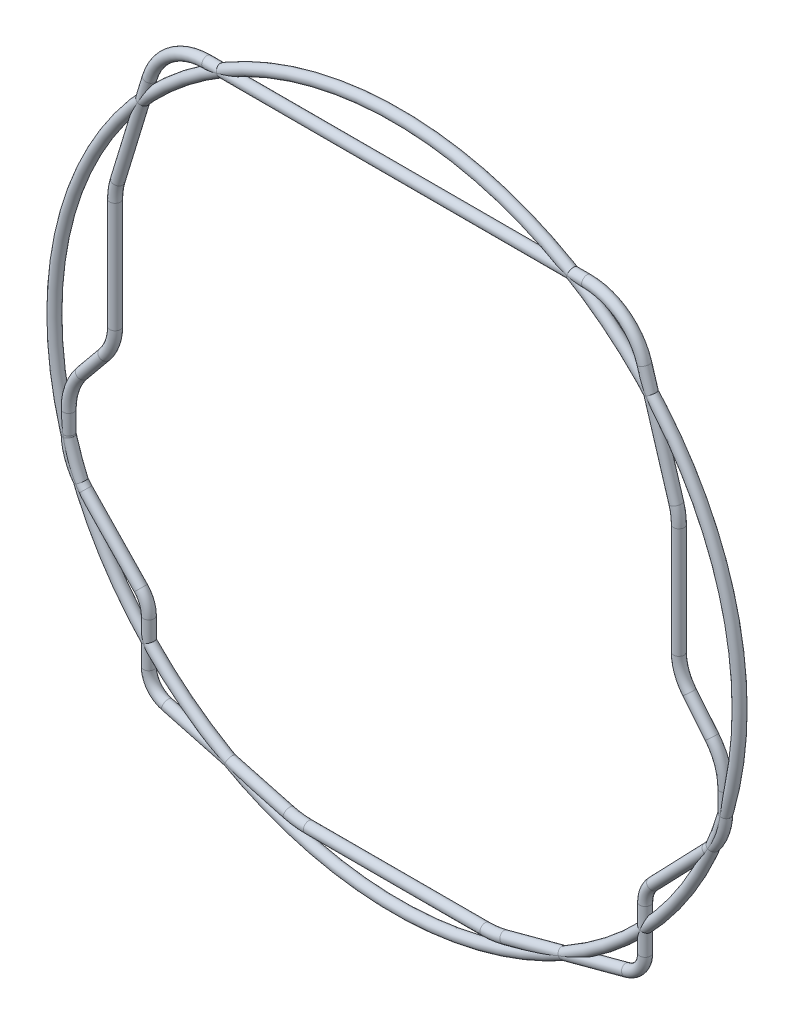
SolidWorks part; units mm, degrees
ref_plane "Front Plane" through (0, 0, 0) normal (0, 0, 1) x (1, 0, 0)
ref_plane "Top Plane" through (0, 0, 0) normal (0, 1, 0) x (1, 0, 0)
ref_plane "Right Plane" through (0, 0, 0) normal (1, 0, 0) x (0, 0, -1)
sketch "Sketch1" plane through (0, 0, 0) normal (0, 0, 1) x (1, 0, 0)
  line L0 (0, 0) -> (126.8104, 0) construction
  line L1 (-24.867, -87.5) -> (0, -87.5) construction
  line L2 (-53.5, 81) -> (53.5, 81) construction
  line L3 (67.8489, 70.3715) -> (76.8489, 40.8305) construction
  line L4 (77.5, 36.459) -> (77.5, 5.3573) construction
  line L5 (80.8939, -4.1452) -> (87.2061, -11.8548) construction
  line L6 (90.6, -21.3573) -> (90.6, -26.8454) construction
  line L7 (70.7917, -53.4876) -> (86.4125, -37.242) construction
  line L8 (68, -60.4187) -> (68, -72.8114) construction
  line L9 (64.2941, -77.6411) -> (30.0433, -86.8185) construction
  line L10 (24.867, -87.5) -> (0, -87.5) construction
  line L11 (-53.5, 82.9) -> (53.5, 82.9)
  line L12 (-64.2941, -77.6411) -> (-30.0433, -86.8185) construction
  line L13 (-68, -60.4187) -> (-68, -72.8114) construction
  line L14 (-70.7917, -53.4876) -> (-86.4125, -37.242) construction
  line L15 (-90.6, -21.3573) -> (-90.6, -26.8454) construction
  line L16 (-80.8939, -4.1452) -> (-87.2061, -11.8548) construction
  line L17 (-77.5, 36.459) -> (-77.5, 5.3573) construction
  line L18 (-67.8489, 70.3715) -> (-76.8489, 40.8305) construction
  line L19 (69.6664, 70.9253) -> (78.6664, 41.3842)
  line L20 (79.4, 36.459) -> (79.4, 5.3573)
  line L21 (82.364, -2.9415) -> (88.6762, -10.6512)
  line L22 (92.5, -21.3573) -> (92.5, -26.8454)
  line L23 (72.1613, -54.8045) -> (87.7821, -38.5589)
  line L24 (69.9, -60.4187) -> (69.9, -72.8114)
  line L25 (64.7859, -79.4763) -> (30.5351, -88.6538)
  line L26 (24.867, -89.4) -> (0, -89.4)
  line L27 (-24.867, -89.4) -> (0, -89.4)
  line L28 (-64.7859, -79.4763) -> (-30.5351, -88.6538)
  line L29 (-69.9, -60.4187) -> (-69.9, -72.8114)
  line L30 (-72.1613, -54.8045) -> (-87.7821, -38.5589)
  line L31 (-92.5, -21.3573) -> (-92.5, -26.8454)
  line L32 (-82.364, -2.9415) -> (-88.6762, -10.6512)
  line L33 (-79.4, 36.459) -> (-79.4, 5.3573)
  line L34 (-69.6664, 70.9253) -> (-78.6664, 41.3842)
  line L36 (0, 0) -> (0, 106.8179) construction
  arc A0 (53.5, 82.9) -> (69.6664, 70.9253) centre (53.5, 66) cw
  arc A1 (77.5, 5.3573) -> (80.8939, -4.1452) centre (92.5, 5.3573) ccw construction
  arc A2 (87.2061, -11.8548) -> (90.6, -21.3573) centre (75.6, -21.3573) cw construction
  arc A3 (90.6, -26.8454) -> (86.4125, -37.242) centre (75.6, -26.8454) cw construction
  arc A4 (76.8489, 40.8305) -> (77.5, 36.459) centre (62.5, 36.459) cw construction
  arc A5 (53.5, 81) -> (67.8489, 70.3715) centre (53.5, 66) cw construction
  arc A6 (70.7917, -53.4876) -> (68, -60.4187) centre (78, -60.4187) ccw construction
  arc A7 (68, -72.8114) -> (64.2941, -77.6411) centre (63, -72.8114) cw construction
  arc A8 (30.0433, -86.8185) -> (24.867, -87.5) centre (24.867, -67.5) cw construction
  arc A9 (-30.0433, -86.8185) -> (-24.867, -87.5) centre (-24.867, -67.5) ccw construction
  arc A10 (-68, -72.8114) -> (-64.2941, -77.6411) centre (-63, -72.8114) ccw construction
  arc A11 (-70.7917, -53.4876) -> (-68, -60.4187) centre (-78, -60.4187) cw construction
  arc A12 (-53.5, 81) -> (-67.8489, 70.3715) centre (-53.5, 66) ccw construction
  arc A13 (-76.8489, 40.8305) -> (-77.5, 36.459) centre (-62.5, 36.459) ccw construction
  arc A14 (-90.6, -26.8454) -> (-86.4125, -37.242) centre (-75.6, -26.8454) ccw construction
  arc A15 (-87.2061, -11.8548) -> (-90.6, -21.3573) centre (-75.6, -21.3573) ccw construction
  arc A16 (-77.5, 5.3573) -> (-80.8939, -4.1452) centre (-92.5, 5.3573) cw construction
  arc A17 (78.6664, 41.3842) -> (79.4, 36.459) centre (62.5, 36.459) cw
  arc A18 (79.4, 5.3573) -> (82.364, -2.9415) centre (92.5, 5.3573) ccw
  arc A19 (88.6762, -10.6512) -> (92.5, -21.3573) centre (75.6, -21.3573) cw
  arc A20 (92.5, -26.8454) -> (87.7821, -38.5589) centre (75.6, -26.8454) cw
  arc A21 (72.1613, -54.8045) -> (69.9, -60.4187) centre (78, -60.4187) ccw
  arc A22 (69.9, -72.8114) -> (64.7859, -79.4763) centre (63, -72.8114) cw
  arc A23 (30.5351, -88.6538) -> (24.867, -89.4) centre (24.867, -67.5) cw
  arc A24 (-30.5351, -88.6538) -> (-24.867, -89.4) centre (-24.867, -67.5) ccw
  arc A25 (-69.9, -72.8114) -> (-64.7859, -79.4763) centre (-63, -72.8114) ccw
  arc A26 (-72.1613, -54.8045) -> (-69.9, -60.4187) centre (-78, -60.4187) cw
  arc A27 (-92.5, -26.8454) -> (-87.7821, -38.5589) centre (-75.6, -26.8454) ccw
  arc A28 (-88.6762, -10.6512) -> (-92.5, -21.3573) centre (-75.6, -21.3573) ccw
  arc A29 (-79.4, 5.3573) -> (-82.364, -2.9415) centre (-92.5, 5.3573) cw
  arc A30 (-78.6664, 41.3842) -> (-79.4, 36.459) centre (-62.5, 36.459) ccw
  arc A31 (-53.5, 82.9) -> (-69.6664, 70.9253) centre (-53.5, 66) ccw
  point P57 (0, 81)
  point P102 (70.1123, -64.4364)
  point P103 (68, -64.4364)
  point P104 (71.611, -59.4574)
  point P106 (0, 0)
  point P107 (71.611, -59.4574)
  point P108 (68, -63.607)
  point P109 (70.2285, -63.607)
  point P110 (0, 0)
  point P111 (-68, -60.4187)
  dimension "D5" = 10
  dimension "D12" = 87.5
  dimension "D13" = 36.459
  dimension "D14" = 21.3573
  dimension "D15" = 78.618
  dimension "D16" = 49.7339
  dimension "D3" = 15
  dimension "D4" = 15
  dimension "D6" = 5
  dimension "D7" = 20
  dimension "D8" = 107
  dimension "D17" = 60.4187
  dimension "D18" = 87.754
  dimension "D19" = 26.8454
  dimension "D1" = 168.5
  dimension "D2" = 15
  dimension "D9" = 155
  dimension "D10" = 181.2
  dimension "D11" = 136
  dimension "D21" = 1.9
sketch "Sketch2" plane through (0, 0, 0) normal (1, 0, 0) x (0, 0, -1)
  line L0 (0, -88.6538) -> (0, -89.4) construction
  circle A0 centre (0, -89.4) radius 1.5
  dimension "D1" = 3
sweep "Sweep1" add profiles "Sketch2" path "Sketch1"
sketch "Sketch3" plane through (0, 0, 0) normal (1, 0, 0) x (0, 0, -1)
  line L0 (0, 0) -> (63.4243, 0) construction
  circle A0 centre (0, 96.5) radius 1.5
  dimension "D1" = 3
  dimension "D2" = 190
revolve "Revolve1" add sketch "Sketch3" angle 360 about L0
sketch "Sketch4" [suppressed] plane through (0, 0, 0) normal (0, 0, 1) x (1, 0, 0)
  line L0 (0, 0) -> (113.8842, 0) construction
  line L1 (0, 0) -> (0, 100.6817) construction
  line L2 (-83.1, 65.075) -> (-83.1, -45.129) construction
  line L3 (83.1, 65.075) -> (83.1, -45.129) construction
  line L4 (-68.1, 80.075) -> (68.1, 80.075) construction
  line L5 (-48.154, -80.075) -> (48.154, -80.075) construction
  line L6 (-78.7066, -55.7356) -> (-58.7606, -75.6816) construction
  line L7 (78.7066, -55.7356) -> (58.7606, -75.6816) construction
  line L14 (-48.154, -82.075) -> (48.154, -82.075)
  line L15 (80.1208, -57.1498) -> (60.1748, -77.0958)
  line L16 (85.1, 65.075) -> (85.1, -45.129)
  line L17 (-68.1, 82.075) -> (68.1, 82.075)
  line L18 (-85.1, 65.075) -> (-85.1, -45.129)
  line L19 (-80.1208, -57.1498) -> (-60.1748, -77.0958)
  arc A0 (83.1, 65.075) -> (68.1, 80.075) centre (68.1, 65.075) ccw construction
  arc A1 (-68.1, 80.075) -> (-83.1, 65.075) centre (-68.1, 65.075) ccw construction
  arc A2 (78.7066, -55.7356) -> (83.1, -45.129) centre (68.1, -45.129) ccw construction
  arc A3 (58.7606, -75.6816) -> (48.154, -80.075) centre (48.154, -65.075) cw construction
  arc A4 (-58.7606, -75.6816) -> (-48.154, -80.075) centre (-48.154, -65.075) ccw construction
  arc A5 (-78.7066, -55.7356) -> (-83.1, -45.129) centre (-68.1, -45.129) cw construction
  arc A12 (60.1748, -77.0958) -> (48.154, -82.075) centre (48.154, -65.075) cw
  arc A13 (80.1208, -57.1498) -> (85.1, -45.129) centre (68.1, -45.129) ccw
  arc A14 (85.1, 65.075) -> (68.1, 82.075) centre (68.1, 65.075) ccw
  arc A15 (-68.1, 82.075) -> (-85.1, 65.075) centre (-68.1, 65.075) ccw
  arc A16 (-80.1208, -57.1498) -> (-85.1, -45.129) centre (-68.1, -45.129) cw
  arc A17 (-60.1748, -77.0958) -> (-48.154, -82.075) centre (-48.154, -65.075) ccw
  dimension "D3" = 15
  dimension "D6" = 15
  dimension "D1" = 166.2
  dimension "D2" = 160.15
  dimension "D4" = 80.075
  dimension "D5" = 45
  dimension "D7" = 45
  dimension "D8" = 45.129
  dimension "D9" = 2
sketch "Sketch5" [suppressed] plane through (0, 0, 0) normal (1, 0, 0) x (0, 0, -1)
  circle A0 centre (0, 82.075) radius 1.5
  dimension "D1" = 3
sweep "RD927 Sweep2" [suppressed] add profiles "Sketch5" path "Sketch4"
